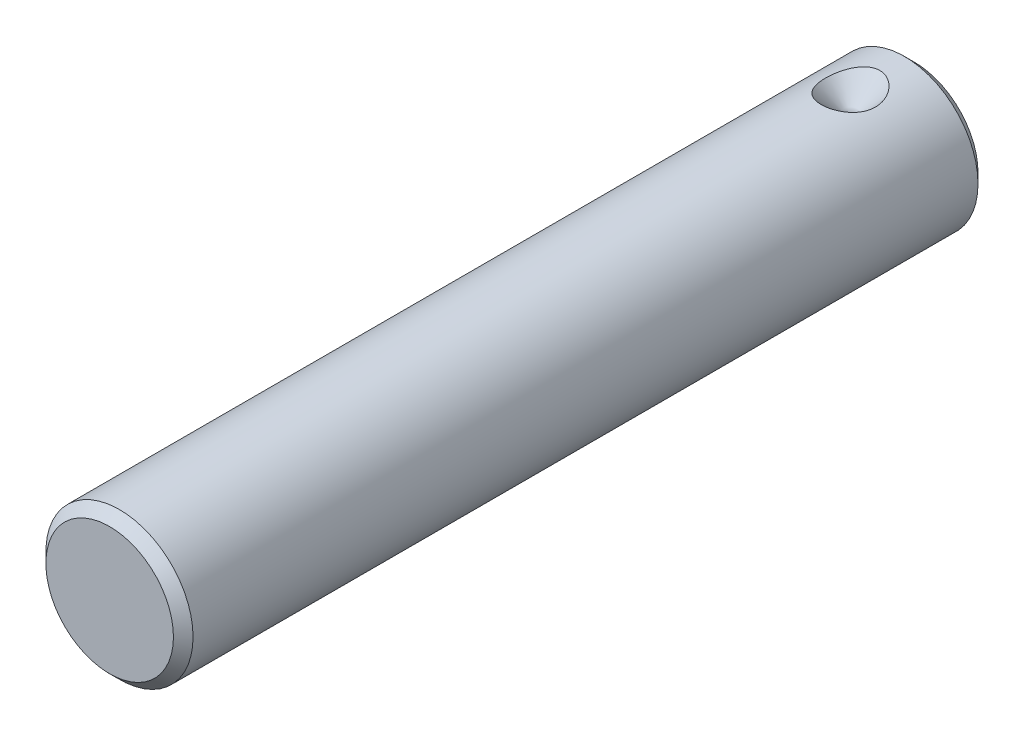
SolidWorks part; units mm, degrees
ref_plane "前视基准面" through (0, 0, 0) normal (0, 0, 1) x (1, 0, 0)
ref_plane "上视基准面" through (0, 0, 0) normal (0, 1, 0) x (1, 0, 0)
ref_plane "右视基准面" through (0, 0, 0) normal (1, 0, 0) x (0, 0, -1)
sketch "草图1" plane through (0, 0, 0) normal (0, 0, 1) x (1, 0, 0)
  circle A0 centre (0, 0) radius 7.5
  dimension "D1" = 15
extrude "凸台-拉伸1" add sketch "草图1" along normal blind 82
sketch "草图2" plane through (0, 0, 0) normal (1, 0, 0) x (0, 0, -1)
  line L0 (-6.5, 21.071) -> (-6.5, -18.8919) construction
  line L1 (-6.5, 4.5) -> (-3.5, 7.5)
  line L2 (0, 7.5) -> (-82, 7.5) construction
  line L3 (-6.5, 4.5) -> (-9.5, 7.5) construction
  line L4 (-3.5, 7.5) -> (-6.5, 7.5)
  line L5 (0, -7.5) -> (0, 7.5) construction
  line L6 (-6.5, 4.5) -> (-6.5, 7.5)
  dimension "D1" = 90
  dimension "D2" = 3
  dimension "D3" = 6.5
revolve "切除-旋转1" cut sketch "草图2" angle 360 about L0
chamfer "倒角1" distance 1 angle 45 2 edges at (7.5, 0, 82) (7.5, 0, 0)
